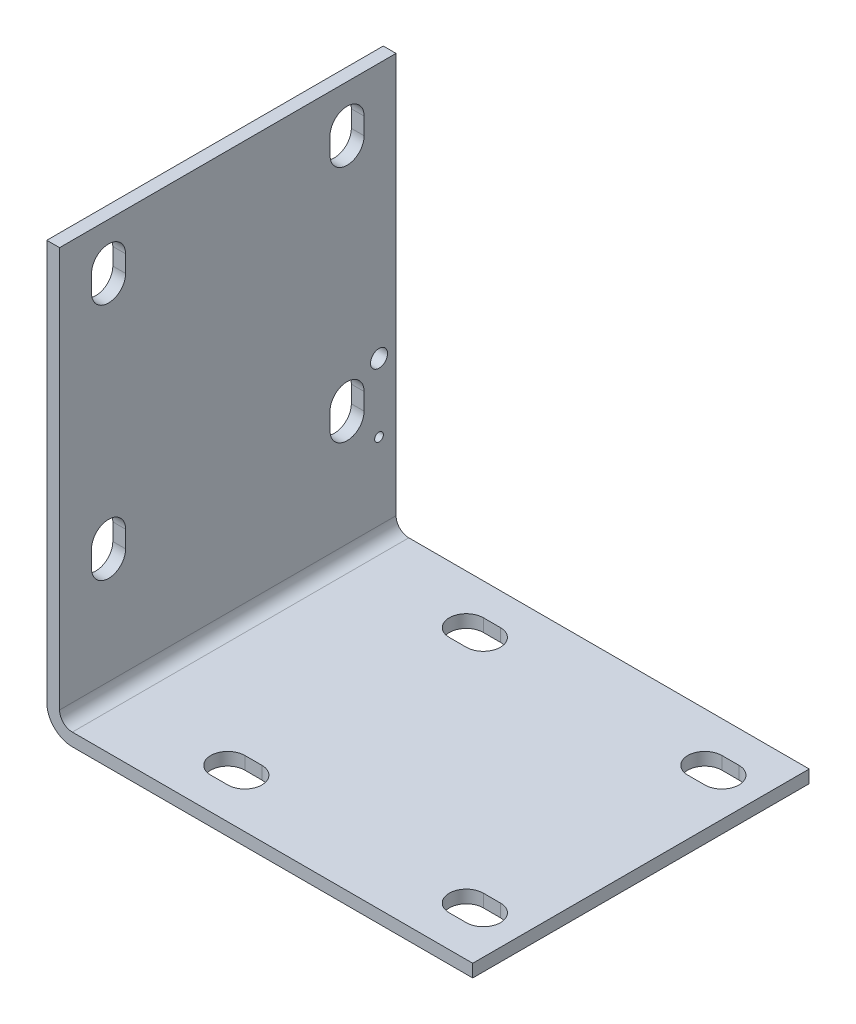
SolidWorks part; units mm, degrees
ref_plane "Front Plane" through (0, 0, 0) normal (0, 0, 1) x (1, 0, 0)
ref_plane "Top Plane" through (0, 0, 0) normal (0, 1, 0) x (1, 0, 0)
ref_plane "Right Plane" through (0, 0, 0) normal (1, 0, 0) x (0, 0, -1)
sketch "Sketch1" plane through (0, 0, 0) normal (0, 0, 1) x (1, 0, 0)
  line L0 (-9.525, 149.225) -> (-4.7625, 149.225)
  line L1 (-4.7625, 149.225) -> (-4.7625, 0)
  line L2 (0, -4.7625) -> (149.225, -4.7625)
  line L3 (149.225, -4.7625) -> (149.225, -9.525)
  line L4 (149.225, -9.525) -> (0, -9.525)
  line L5 (-9.525, 0) -> (-9.525, 149.225)
  arc A0 (-4.7625, 0) -> (0, -4.7625) centre (0, 0) ccw
  arc A1 (0, -9.525) -> (-9.525, 0) centre (0, 0) cw
  dimension "D4" = 4.7625
  dimension "D1" = 158.75
  dimension "D2" = 4.7625
  dimension "D3" = 158.75
extrude "Boss-Extrude1" add sketch "Sketch1" along normal mid plane 125.4125
ref_plane "Plane1" through (0, 0, 0) normal (0.7071, -0.7071, 0) x (-0.7071, -0.7071, 0)
sketch "Sketch2" plane through (-4.7625, 0, 0) normal (1, 0, 0) x (0, 0, -1)
  line L0 (-50.8, 134.9375) -> (-50.8, 128.5875)
  line L1 (-38.1, 128.5875) -> (-38.1, 134.9375)
  line L2 (-50.8, 46.0375) -> (-50.8, 39.6875)
  line L3 (-38.1, 39.6875) -> (-38.1, 46.0375)
  line L4 (38.1, 39.6875) -> (38.1, 46.0375)
  line L5 (50.8, 46.0375) -> (50.8, 39.6875)
  line L6 (38.1, 134.9375) -> (38.1, 128.5875)
  line L7 (50.8, 128.5875) -> (50.8, 134.9375)
  line L8 (-62.7063, 149.225) -> (62.7063, 149.225) construction
  line L9 (-44.45, 134.9375) -> (44.45, 134.9375) construction
  arc A0 (-50.8, 128.5875) -> (-38.1, 128.5875) centre (-44.45, 128.5875) ccw
  arc A1 (-38.1, 134.9375) -> (-50.8, 134.9375) centre (-44.45, 134.9375) ccw
  arc A2 (-50.8, 39.6875) -> (-38.1, 39.6875) centre (-44.45, 39.6875) ccw
  arc A3 (-38.1, 46.0375) -> (-50.8, 46.0375) centre (-44.45, 46.0375) ccw
  arc A4 (38.1, 46.0375) -> (50.8, 46.0375) centre (44.45, 46.0375) cw
  arc A5 (50.8, 39.6875) -> (38.1, 39.6875) centre (44.45, 39.6875) cw
  arc A6 (38.1, 128.5875) -> (50.8, 128.5875) centre (44.45, 128.5875) ccw
  arc A7 (50.8, 134.9375) -> (38.1, 134.9375) centre (44.45, 134.9375) ccw
  point P23 (0, 134.9375)
  point P29 (-44.45, 141.2875)
  point P30 (-44.45, 122.2375)
  point P34 (-44.45, 52.3875)
  dimension "D1" = 12.7
  dimension "D2" = 19.05
  dimension "D3" = 7.9375
  dimension "D4" = 69.85
  dimension "D5" = 76.2
extrude "Cut-Extrude1" cut sketch "Sketch2" against normal through all
mirror "Mirror1" about plane through (0, 0, 0) normal (0.7071, -0.7071, 0) of "Cut-Extrude1"
sketch "Sketch3" plane through (-4.7625, 0, 0) normal (1, 0, 0) x (0, 0, -1)
  line L0 (-62.7063, -9.525) -> (62.7063, -9.525) construction
  line L2 (62.7063, 0) -> (62.7063, 149.225) construction
  circle A0 centre (56.3563, 28.575) radius 1.625
  circle A1 centre (56.3563, 53.975) radius 3.175
  dimension "D1" = 3.25
  dimension "D2" = 6.35
  dimension "D3" = 38.1
  dimension "D4" = 25.4
  dimension "D5" = 6.35
extrude "Cut-Extrude2" cut sketch "Sketch3" against normal through all
